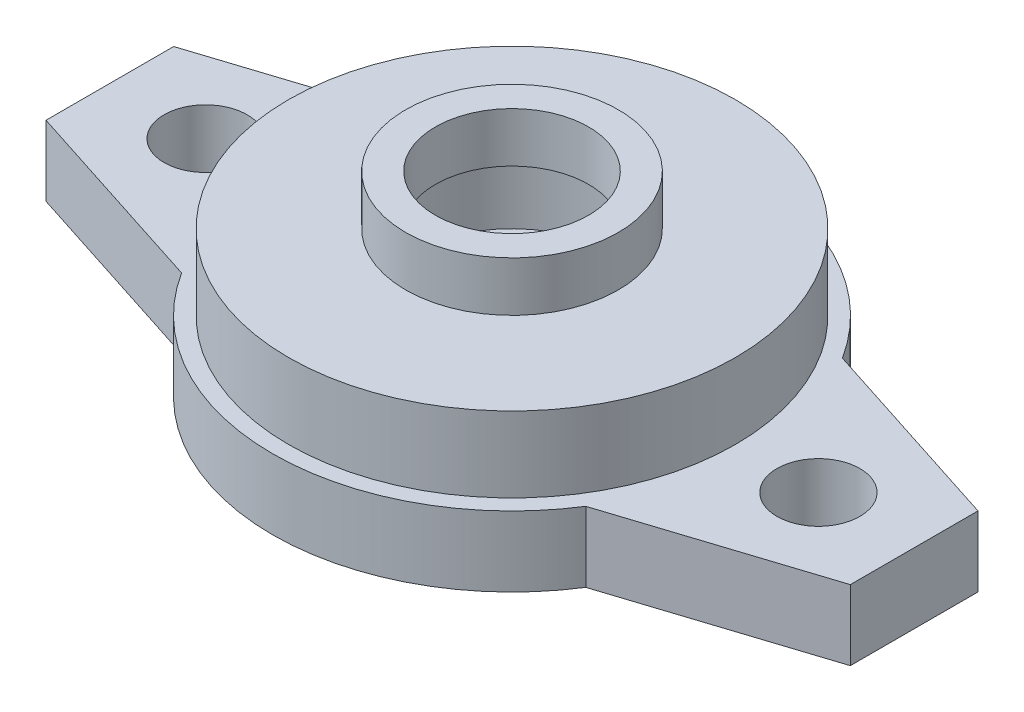
SolidWorks part; units mm, degrees
ref_plane "Front Plane" through (0, 0, 0) normal (0, 0, 1) x (1, 0, 0)
ref_plane "Top Plane" through (0, 0, 0) normal (0, 1, 0) x (1, 0, 0)
ref_plane "Right Plane" through (0, 0, 0) normal (1, 0, 0) x (0, 0, -1)
sketch "Sketch1" plane through (0, 0, 0) normal (0, 1, 0) x (1, 0, 0)
  line L0 (0, 0) -> (15.8291, 0) construction
  line L1 (15.8291, 0) -> (15.8291, 10.05) construction
  line L2 (0, 0) -> (31.5, 0) construction
  line L3 (31.5, 0) -> (31.5, 5)
  line L4 (15.8291, 10.05) -> (15.8291, -10.05) construction
  line L5 (31.5, 5) -> (15.8291, 10.05)
  line L6 (31.5, 0) -> (31.5, -5)
  line L7 (31.5, -5) -> (15.8291, -10.05)
  line L8 (0, 0) -> (24, 0) construction
  line L9 (0, 0) -> (0, 18.75) construction
  line L10 (-31.5, -5) -> (-15.8291, -10.05)
  line L11 (-31.5, 0) -> (-31.5, -5)
  line L12 (-31.5, 0) -> (-31.5, 5)
  line L13 (-31.5, 5) -> (-15.8291, 10.05)
  circle A0 centre (0, 0) radius 6
  circle A1 centre (0, 0) radius 18.75
  circle A2 centre (24, 0) radius 3.25
  circle A3 centre (-24, 0) radius 3.25
  dimension "D1" = 12
  dimension "D2" = 37.5
  dimension "D9" = 6.5
  dimension "D3" = 10.05
  dimension "D4" = 31.5
  dimension "D5" = 20.1
  dimension "D6" = 5
  dimension "D7" = 5
  dimension "D8" = 24
extrude "Boss-Extrude1" add sketch "Sketch1" along normal blind 5.5 contours A1 A0 | A1 L13 L12 L11 L10 A3 | A1 L7 L6 L3 L5 A2
sketch "Sketch2" plane through (0, 5.5, 0) normal (0, 1, 0) x (1, 0, 0)
  circle A0 centre (0, 0) radius 17.5
  circle A1 centre (0, 0) radius 8.33
  dimension "D1" = 35
  dimension "D2" = 16.66
extrude "Boss-Extrude2" add sketch "Sketch2" along normal blind 5.9
sketch "Sketch3" plane through (0, 11.4, 0) normal (0, 1, 0) x (1, 0, 0)
  circle A0 centre (0, 0) radius 6
  circle A1 centre (0, 0) radius 8.33
  dimension "D1" = 12
  dimension "D2" = 16.66
extrude "Boss-Extrude3" add sketch "Sketch3" along normal blind 3.9 separate body
